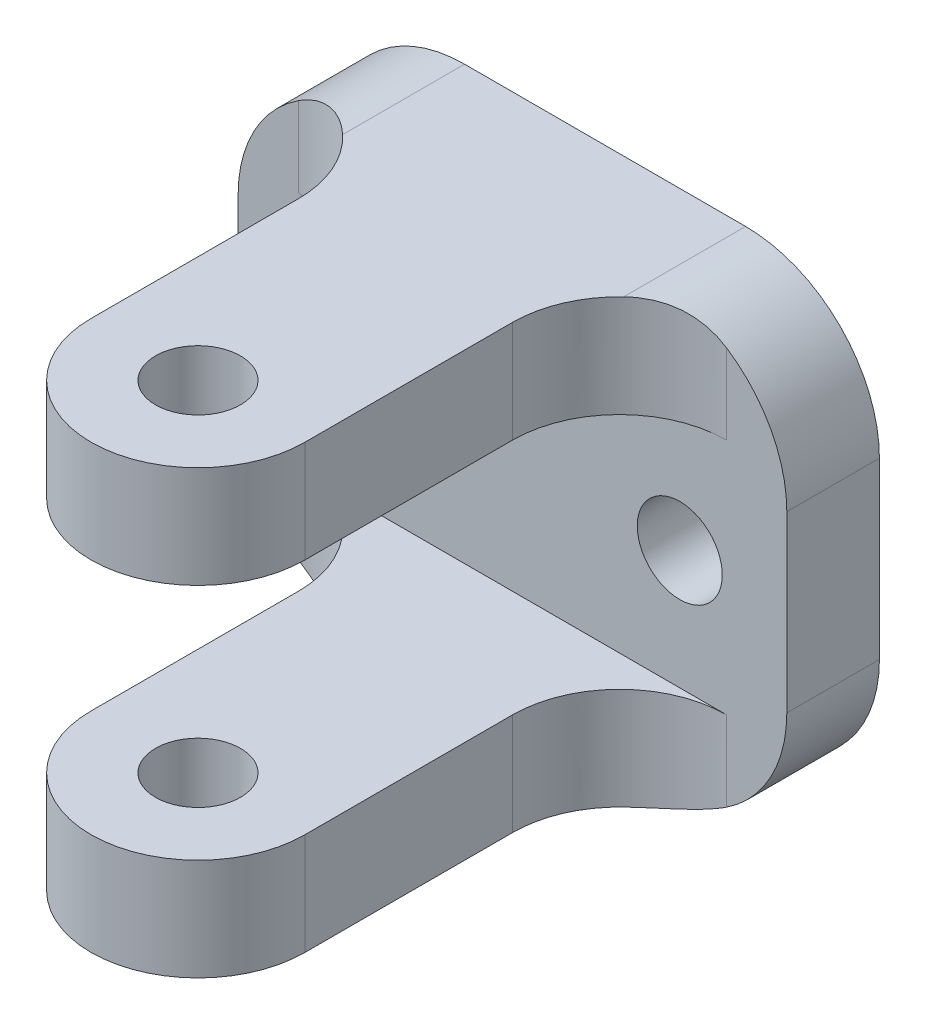
SolidWorks part; units mm, degrees
material "7075-T6 (SN)"
ref_plane "Front Plane" through (0, 0, 0) normal (0, 0, 1) x (1, 0, 0)
ref_plane "Top Plane" through (0, 0, 0) normal (0, 1, 0) x (1, 0, 0)
ref_plane "Right Plane" through (0, 0, 0) normal (1, 0, 0) x (0, 0, -1)
sketch "Sketch1" plane through (0, 0, 0) normal (0, 0, 1) x (1, 0, 0)
  line L0 (12.5, 0) -> (-12.5, 0) construction
  line L1 (-20.5, -16.51) -> (20.5, -16.51)
  line L2 (-20.5, -16.51) -> (-20.5, 16.51)
  line L3 (-20.5, 16.51) -> (20.5, 16.51)
  line L4 (20.5, -16.51) -> (20.5, 16.51)
  line L5 (-20.5, -16.51) -> (20.5, 16.51) construction
  line L6 (-20.5, 16.51) -> (20.5, -16.51) construction
  circle A0 centre (12.5, 0) radius 3.175
  circle A1 centre (-12.5, 0) radius 3.175
  point P0 (0, 0)
  dimension "D1" = 6.35
  dimension "D2" = 25
  dimension "D3" = 8
  dimension "D4" = 16.51
extrude "Boss-Extrude1" add sketch "Sketch1" along normal blind 12 contours L3 L4 L1 L2
sketch "Sketch2" plane through (0, 0, 12) normal (0, 0, 1) x (1, 0, 0)
  line L0 (-12.5, 0) -> (12.5, 0) construction
  line L2 (-20.5, 8.89) -> (20.5, 8.89)
  line L3 (-20.5, 8.89) -> (-20.5, 16.51)
  line L4 (-20.5, 16.51) -> (20.5, 16.51)
  line L5 (20.5, 8.89) -> (20.5, 16.51)
  line L6 (-20.5, 8.89) -> (20.5, 16.51) construction
  line L7 (-20.5, 16.51) -> (20.5, 8.89) construction
  line L8 (-20.5, 16.51) -> (-20.5, -16.51) construction
  line L9 (20.5, -8.89) -> (20.5, -16.51)
  line L10 (-20.5, -8.89) -> (-20.5, -16.51)
  line L11 (-20.5, -16.51) -> (20.5, -8.89) construction
  line L12 (-20.5, -8.89) -> (20.5, -16.51) construction
  line L13 (-20.5, -8.89) -> (20.5, -8.89)
  line L14 (-20.5, -16.51) -> (20.5, -16.51)
  circle A0 centre (-12.5, 0) radius 3.175 construction
  circle A1 centre (12.5, 0) radius 3.175 construction
  point P6 (0, 12.7)
  point P21 (0, -12.7)
  dimension "D1" = 17.78
extrude "Boss-Extrude2" add sketch "Sketch2" along normal blind 53
sketch "Sketch3" plane through (0, 0, 0) normal (0, 1, 0) x (1, 0, 0)
  point P0 (0, -35.5)
  dimension "D1" = 35.5
ref_point "UBJ Point"
sketch "Sketch4" plane through (0, 0, 0) normal (0, 1, 0) x (1, 0, 0)
  circle A0 centre (0, -35.5) radius 3.175
  dimension "D1" = 6.35
extrude "Cut-Extrude1" cut sketch "Sketch4" against normal up to surface and the other way up to surface up to face at (0, -16.51, 32.5) other way up to face at (0, 16.51, 32.5)
sketch "Sketch5" plane through (0, 0, 0) normal (0, 1, 0) x (1, 0, 0)
  line L0 (20.5, -12) -> (8.3825, -39.2302)
  line L1 (-8.3825, -39.2302) -> (-20.5, -12)
  line L4 (20.5, 0) -> (-20.5, 0)
  line L5 (-20.5, 0) -> (-20.5, -65)
  line L6 (-20.5, -65) -> (20.5, -65)
  line L7 (20.5, -65) -> (20.5, 0)
  line L9 (-20.5, -12) -> (-20.5, -65)
  line L10 (-20.5, -65) -> (20.5, -65)
  line L11 (20.5, -65) -> (20.5, -12)
  line L12 (20.5, -12) -> (-20.5, -12)
  line L13 (20.5, -65) -> (20.5, -12)
  line L14 (-20.5, -65) -> (20.5, -65)
  line L15 (-20.5, -12) -> (-20.5, -65)
  line L17 (20.5, -65) -> (20.5, -12)
  line L18 (-20.5, -65) -> (20.5, -65)
  line L19 (-20.5, -12) -> (-20.5, -65)
  arc A0 (-8.3825, -39.2302) -> (8.3825, -39.2302) centre (0, -35.5) ccw
  circle A1 centre (0, -35.5) radius 3.175 construction
  circle A2 centre (0, -35.5) radius 3.175 construction
  dimension "D3" = 6
  dimension "D1" = 0
  dimension "D2" = 0
extrude "Cut-Extrude2" [suppressed] cut sketch "Sketch5" against normal up to surface and the other way up to surface contours A0 L1 L9 L10 L11 L0
sketch "Sketch6" plane through (0, 0, 0) normal (0, 1, 0) x (1, 0, 0)
  line L0 (-8, -35.5) -> (-8, -20)
  line L1 (8, -35.5) -> (8, -20)
  line L2 (-16, -12) -> (-20.5, -12)
  line L4 (20.5, -12) -> (-20.5, -12)
  line L5 (-20.5, -12) -> (-20.5, -65)
  line L6 (-20.5, -65) -> (20.5, -65)
  line L7 (20.5, -65) -> (20.5, -12)
  line L8 (20.5, -12) -> (16, -12)
  line L9 (-20.5, -12) -> (-20.5, -65)
  line L10 (-20.5, -65) -> (20.5, -65)
  line L11 (20.5, -65) -> (20.5, -12)
  arc A0 (-8, -35.5) -> (8, -35.5) centre (0, -35.5) ccw
  circle A1 centre (0, -35.5) radius 3.175 construction
  arc A2 (-8, -20) -> (-16, -12) centre (-16, -20) ccw
  arc A3 (8, -20) -> (16, -12) centre (16, -20) cw
  dimension "D2" = 8
  dimension "D3" = 8
  dimension "D1" = 0
extrude "Cut-Extrude3" cut sketch "Sketch6" against normal up to surface and the other way up to surface up to face at (0, -16.51, 38.675) other way up to face at (0, 16.51, 32.325)
fillet "Fillet1" radius 10 4 edges at (-20.5, -16.51, 6) (-20.5, 16.51, 6) (20.5, -16.51, 6) (20.5, 16.51, 6)
sketch "Sketch7" plane through (0, 0, 0) normal (0, 0, -1) x (-1, 0, 0)
  line L4 (-10.5, -16.51) -> (10.5, -16.51)
  line L5 (20.5, -6.51) -> (20.5, 6.51)
  line L6 (10.5, 16.51) -> (-10.5, 16.51)
  line L7 (-20.5, 6.51) -> (-20.5, -6.51)
  line L8 (-10.5, -16.51) -> (10.5, -16.51)
  line L9 (20.5, -6.51) -> (20.5, 6.51)
  line L10 (10.5, 16.51) -> (-10.5, 16.51)
  line L11 (-20.5, 6.51) -> (-20.5, -6.51)
  arc A4 (10.5, -16.51) -> (20.5, -6.51) centre (10.5, -6.51) ccw
  arc A5 (20.5, 6.51) -> (10.5, 16.51) centre (10.5, 6.51) ccw
  arc A6 (-10.5, 16.51) -> (-20.5, 6.51) centre (-10.5, 6.51) ccw
  arc A7 (-20.5, -6.51) -> (-10.5, -16.51) centre (-10.5, -6.51) ccw
  arc A8 (10.5, -16.51) -> (20.5, -6.51) centre (10.5, -6.51) ccw
  arc A9 (20.5, 6.51) -> (10.5, 16.51) centre (10.5, 6.51) ccw
  arc A10 (-10.5, 16.51) -> (-20.5, 6.51) centre (-10.5, 6.51) ccw
  arc A11 (-20.5, -6.51) -> (-10.5, -16.51) centre (-10.5, -6.51) ccw
  dimension "D1" = 0
extrude "Cut-Extrude4" cut sketch "Sketch7" against normal blind 5.08
